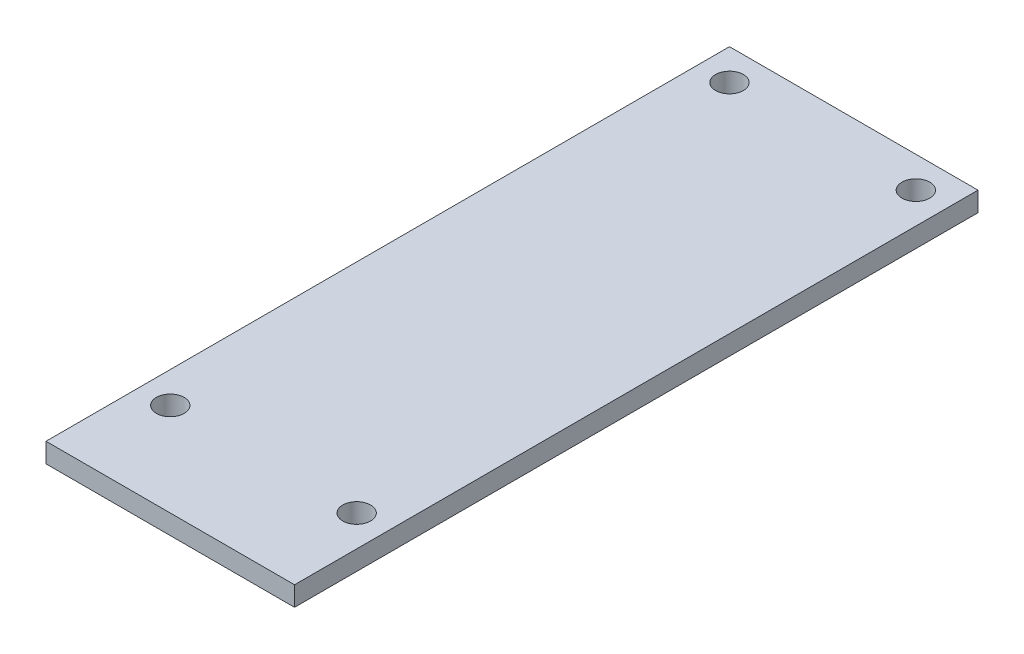
SolidWorks part; units mm, degrees
material "Custom Plastic"
ref_plane "Front Plane" through (0, 0, 0) normal (0, 0, 1) x (1, 0, 0)
ref_plane "Top Plane" through (0, 0, 0) normal (0, 1, 0) x (1, 0, 0)
ref_plane "Right Plane" through (0, 0, 0) normal (1, 0, 0) x (0, 0, -1)
sketch "Sketch1" plane through (0, 0, 0) normal (0, 1, 0) x (1, 0, 0)
  line L1 (0, 0) -> (25.4, 0)
  line L2 (0, 0) -> (0, 69.85)
  line L3 (0, 69.85) -> (25.4, 69.85)
  line L4 (25.4, 0) -> (25.4, 69.85)
  dimension "D1" = 69.85
  dimension "D2" = 25.4
extrude "Boss-Extrude1" add sketch "Sketch1" along normal blind 2
sketch "Sketch2" plane through (0, 2, 0) normal (0, 1, 0) x (1, 0, 0)
  line L0 (3.175, 69.85) -> (3.175, 0) construction
  line L1 (25.4, 69.85) -> (0, 69.85) construction
  line L2 (22.225, 69.85) -> (22.225, 0) construction
  line L3 (0, 0) -> (25.4, 0) construction
  line L4 (0, 66.675) -> (25.4, 66.675) construction
  line L5 (0, 69.85) -> (0, 0) construction
  line L6 (25.4, 0) -> (25.4, 69.85) construction
  line L7 (0, 9.525) -> (25.4, 9.525) construction
  circle A0 centre (3.175, 66.675) radius 1.4224
  circle A1 centre (22.225, 66.675) radius 1.4224
  circle A2 centre (3.175, 9.525) radius 1.4224
  circle A3 centre (22.225, 9.525) radius 1.4224
  dimension "D5" = 2.8448
  dimension "D6" = 2.8448
  dimension "D7" = 2.8448
  dimension "D8" = 2.8448
  dimension "D1" = 3.175
  dimension "D2" = 3.175
  dimension "D3" = 3.175
  dimension "D4" = 9.525
extrude "Cut-Extrude1" cut sketch "Sketch2" against normal blind 2
